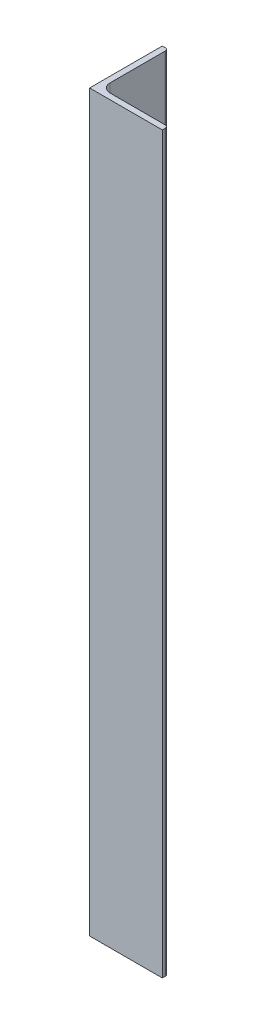
SolidWorks part; units mm, degrees
material "Ст 3"
ref_plane "Спереди" through (0, 0, 0) normal (0, 0, 1) x (1, 0, 0)
ref_plane "Сверху" through (0, 0, 0) normal (0, 1, 0) x (1, 0, 0)
ref_plane "Справа" through (0, 0, 0) normal (1, 0, 0) x (0, 0, -1)
other "Configuration Table"
sketch "Эскиз1" plane through (0, 0, 0) normal (0, 1, 0) x (1, 0, 0)
  line L0 (0, 0) -> (0, 75)
  line L1 (0, 0) -> (75, 0)
  line L2 (75, 0) -> (75, 3)
  line L3 (72, 6) -> (15, 6)
  line L4 (6, 15) -> (6, 72)
  line L5 (3, 75) -> (0, 75)
  arc A0 (15, 6) -> (6, 15) centre (15, 15) cw
  arc A1 (6, 72) -> (3, 75) centre (3, 72) ccw
  arc A2 (75, 3) -> (72, 6) centre (72, 3) ccw
  point P11 (6, 75)
  point P14 (75, 6)
  dimension "D5" = 9
  dimension "D6" = 3
  dimension "D1" = 75
  dimension "D2" = 75
  dimension "D3" = 6
  dimension "D4" = 6
extrude "Бобышка-Вытянуть1" add sketch "Эскиз1" along normal blind 758
sketch "Эскиз2" plane through (0, 0, 0) normal (-1, 0, 0) x (0, 0, 1)
  line L0 (-75, 758) -> (-75, 0) construction
  line L1 (-6, 758) -> (-75, 758)
  line L2 (-6, 758) -> (-6, 718)
  line L3 (-6, 718) -> (-75, 718)
  line L4 (-75, 758) -> (-75, 718)
  dimension "D1" = 40
extrude "Вырез-Вытянуть1" [suppressed] cut sketch "Эскиз2" against normal blind 113
